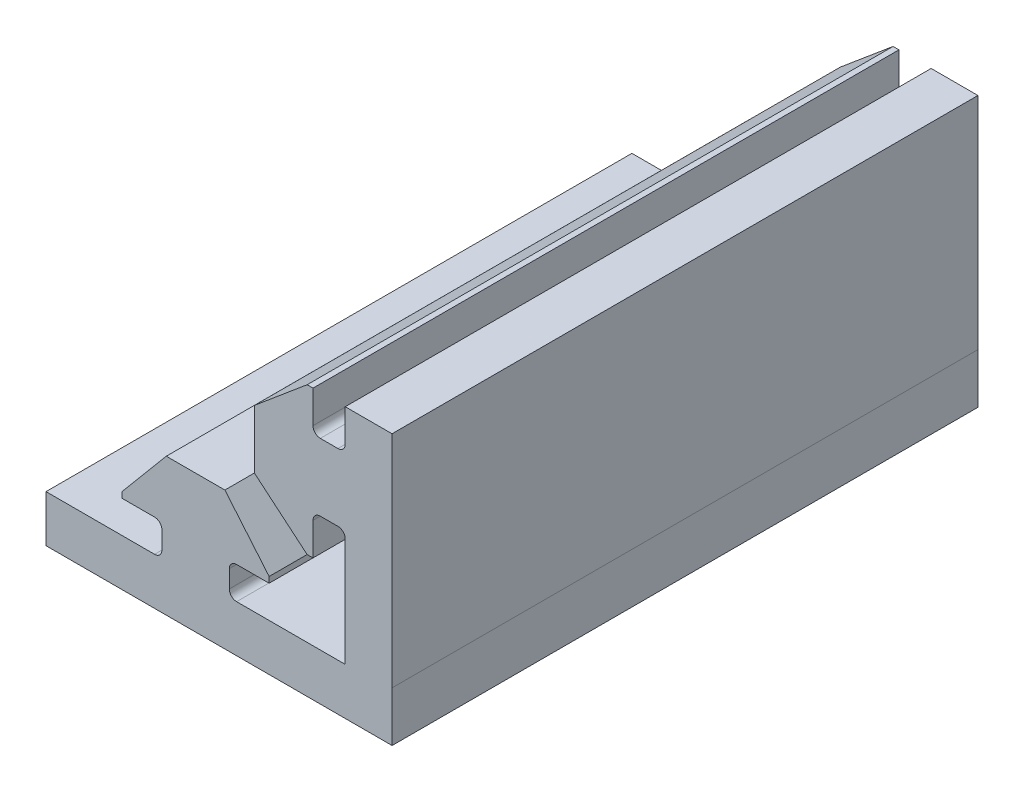
SolidWorks part; units mm, degrees
ref_plane "Front Plane" through (0, 0, 0) normal (0, 0, 1) x (1, 0, 0)
ref_plane "Top Plane" through (0, 0, 0) normal (0, 1, 0) x (1, 0, 0)
ref_plane "Right Plane" through (0, 0, 0) normal (1, 0, 0) x (0, 0, -1)
ref_plane "Plane1" through (0, 0, -3683) normal (0, 0, -1) x (-1, 0, 0)
sketch "Sketch1" plane through (0, 0, -3683) normal (0, 0, -1) x (-1, 0, 0)
  line L0 (7.9453, 3.5889) -> (-1.1987, 3.5889)
  line L1 (-1.8337, 4.2239) -> (-1.8337, 5.7479)
  line L2 (-1.1987, 6.3829) -> (1.6216, 6.3829)
  line L3 (1.6216, 6.3829) -> (1.6216, 6.8909)
  line L4 (1.6216, 6.8909) -> (-2.2147, 11.4629)
  line L5 (-2.2147, 11.4629) -> (-7.2947, 11.4629)
  line L6 (-7.2947, 11.4629) -> (-11.1311, 6.8909)
  line L7 (-11.1311, 6.8909) -> (-11.1311, 6.3829)
  line L8 (-11.1311, 6.3829) -> (-8.3107, 6.3829)
  line L9 (-7.6757, 5.7479) -> (-7.6757, 4.2239)
  line L10 (-8.3107, 3.5889) -> (-17.4547, 3.5889)
  line L11 (-17.7279, 3.8588) -> (-17.7284, 13.0024)
  line L12 (-17.4548, -0.4751) -> (7.9452, -0.4751)
  line L13 (-17.0929, 13.6378) -> (-15.5689, 13.6378)
  line L29 (-17.4547, 3.5889) -> (-17.7279, 3.5889)
  line L30 (-17.4548, -0.4751) -> (-17.7279, -0.4751)
  line L32 (8.2155, 3.5889) -> (8.2155, -0.4751)
  line L34 (8.2155, 3.5889) -> (7.9453, 3.5889)
  line L35 (8.2155, -0.4751) -> (7.9452, -0.4751)
  line L36 (-14.9339, 13.0028) -> (-14.9339, 10.1825)
  line L37 (-14.9339, 10.1825) -> (-14.4259, 10.1825)
  line L38 (-14.4259, 10.1825) -> (-9.8539, 14.0188)
  line L39 (-9.8539, 14.0188) -> (-9.8539, 19.0988)
  line L40 (-9.8539, 19.0988) -> (-14.4259, 22.9352)
  line L41 (-14.4259, 22.9352) -> (-14.9339, 22.9352)
  line L42 (-14.9339, 22.9352) -> (-14.9339, 20.1148)
  line L43 (-15.5689, 19.4798) -> (-17.0929, 19.4798)
  line L44 (-17.7287, 20.1156) -> (-17.7288, 22.9352)
  line L45 (-21.7872, 22.9352) -> (-21.7919, 3.8591)
  line L49 (-17.7288, 22.9352) -> (-21.7872, 22.9352)
  line L51 (-17.7279, 3.5889) -> (-17.7279, 3.8588)
  line L52 (-21.7919, 3.5889) -> (-21.7919, 3.8591)
  line L54 (-17.7279, -0.4751) -> (-21.7919, -0.4751)
  line L56 (-21.7919, -0.4751) -> (-21.7919, 3.5889)
  arc A0 (-1.1987, 3.5889) -> (-1.8337, 4.2239) centre (-1.1987, 4.2239) cw
  arc A1 (-1.8337, 5.7479) -> (-1.1987, 6.3829) centre (-1.1987, 5.7479) cw
  arc A2 (-8.3107, 6.3829) -> (-7.6757, 5.7479) centre (-8.3107, 5.7479) cw
  arc A3 (-7.6757, 4.2239) -> (-8.3107, 3.5889) centre (-8.3107, 4.2239) cw
  arc A4 (-17.7284, 13.0024) -> (-17.0929, 13.6378) centre (-17.0929, 13.0024) cw
  arc A5 (-15.5689, 13.6378) -> (-14.9339, 13.0028) centre (-15.5689, 13.0028) cw
  arc A6 (-14.9339, 20.1148) -> (-15.5689, 19.4798) centre (-15.5689, 20.1148) cw
  arc A7 (-17.0929, 19.4798) -> (-17.7287, 20.1156) centre (-17.0929, 20.1156) cw
extrude "Boss-Extrude1" add sketch "Sketch1" along normal blind 50.8
